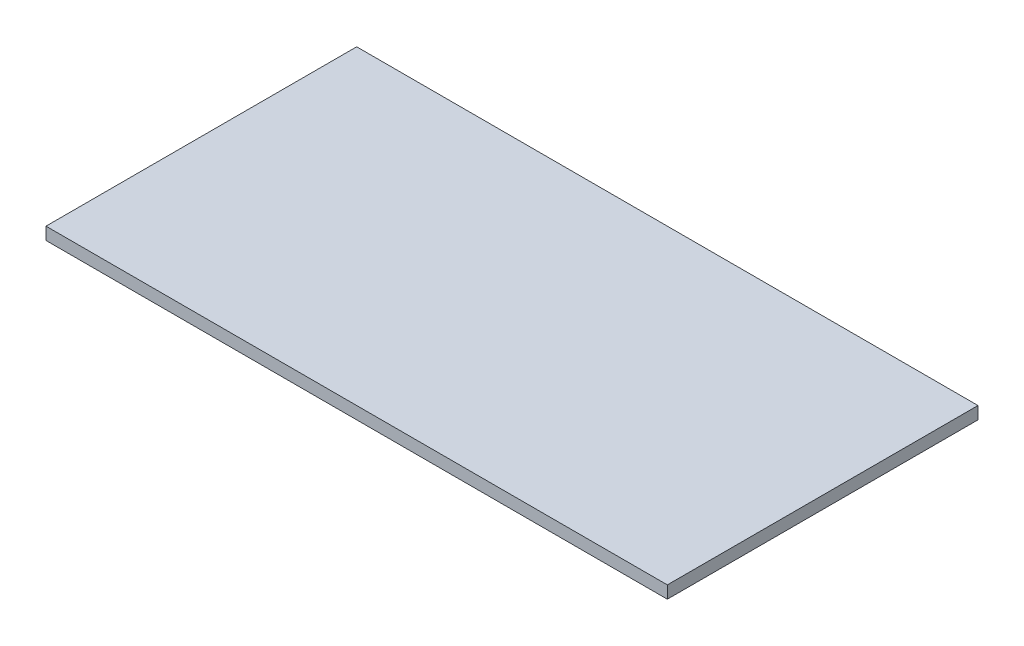
SolidWorks part; units mm, degrees
material "Perspex (TM) GS Acrylic Cast Sheet"
ref_plane "Front Plane" through (0, 0, 0) normal (0, 0, 1) x (1, 0, 0)
ref_plane "Top Plane" through (0, 0, 0) normal (0, 1, 0) x (1, 0, 0)
ref_plane "Right Plane" through (0, 0, 0) normal (1, 0, 0) x (0, 0, -1)
sketch "Sketch1" plane through (0, 0, 0) normal (0, 1, 0) x (1, 0, 0)
  line L1 (0, 0) -> (200, 0)
  line L2 (0, 0) -> (0, 100)
  line L3 (0, 100) -> (200, 100)
  line L4 (200, 0) -> (200, 100)
  dimension "D1" = 200
  dimension "D2" = 100
extrude "Boss-Extrude1" add sketch "Sketch1" along normal blind 4
